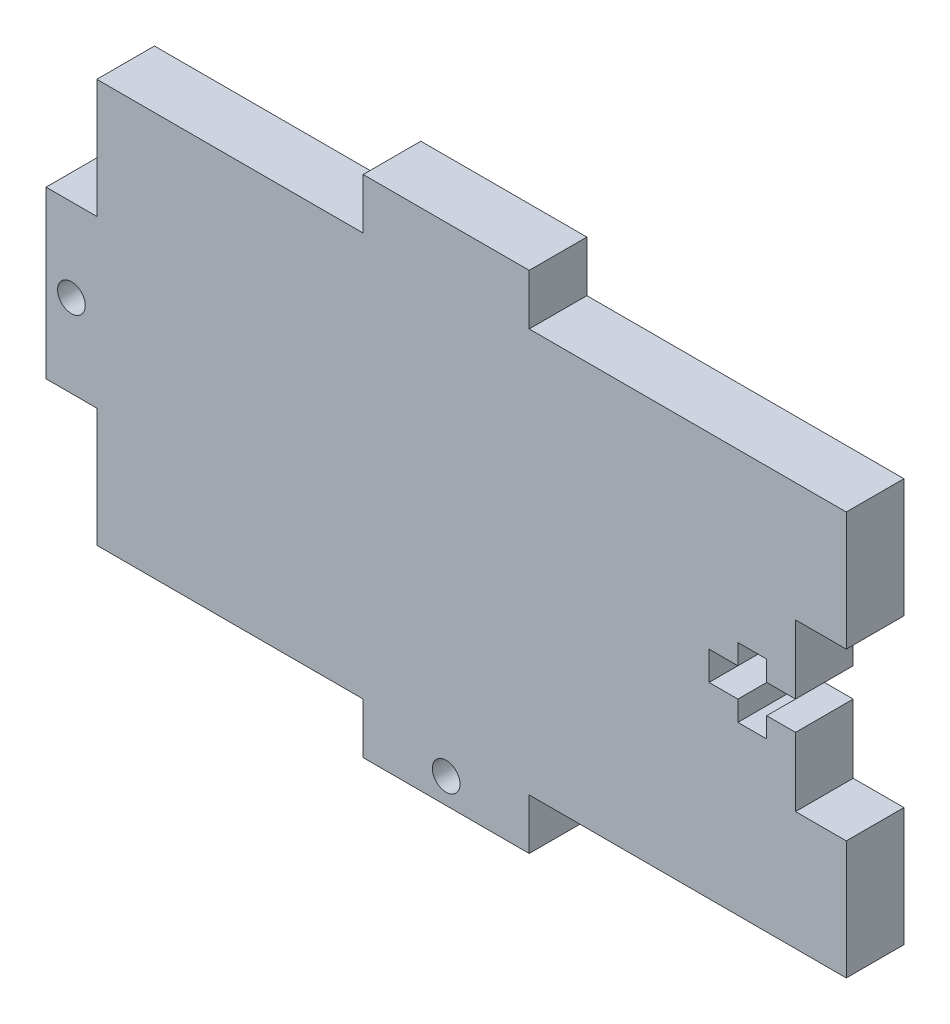
SolidWorks part; units mm, degrees
ref_plane "Front Plane" through (0, 0, 0) normal (0, 0, 1) x (1, 0, 0)
ref_plane "Top Plane" through (0, 0, 0) normal (0, 1, 0) x (1, 0, 0)
ref_plane "Right Plane" through (0, 0, 0) normal (1, 0, 0) x (0, 0, -1)
sketch "Sketch1" plane through (0, 0, 0) normal (0, 0, 1) x (1, 0, 0)
  line L1 (0, 0) -> (82.55, 0)
  line L2 (0, 0) -> (0, 44.45)
  line L3 (0, 44.45) -> (82.55, 44.45)
  line L4 (82.55, 0) -> (82.55, 44.45)
  dimension "D1" = 44.45
  dimension "D2" = 82.55
extrude "Boss-Extrude1" add sketch "Sketch1" along normal blind 6.35
sketch "Sketch2" plane through (0, 0, 6.35) normal (0, 0, 1) x (1, 0, 0)
  line L0 (0, -1.7462) -> (0, 1.7462) construction
  line L1 (0, 31.369) -> (-5.588, 31.369)
  line L2 (0, 31.369) -> (0, 13.081)
  line L3 (0, 13.081) -> (-5.588, 13.081)
  line L4 (-5.588, 31.369) -> (-5.588, 13.081)
  line L6 (0, 44.45) -> (0, 0) construction
  point P6 (-5.588, 22.225)
  point P7 (0, 22.225)
  dimension "D1" = 5.588
  dimension "D2" = 18.288
extrude "Boss-Extrude2" add sketch "Sketch2" against normal blind 6.35
sketch "Sketch5" plane through (0, 0, 6.35) normal (0, 0, 1) x (1, 0, 0)
  line L0 (82.55, 44.45) -> (0, 44.45) construction
  line L1 (29.337, 44.45) -> (47.625, 44.45)
  line L2 (29.337, 44.45) -> (29.337, 50.038)
  line L3 (29.337, 50.038) -> (47.625, 50.038)
  line L4 (47.625, 44.45) -> (47.625, 50.038)
  line L6 (-5.588, 22.225) -> (82.55, 22.225) construction
  line L7 (47.625, 0) -> (47.625, -5.588)
  line L8 (29.337, -5.588) -> (47.625, -5.588)
  line L9 (29.337, 0) -> (29.337, -5.588)
  line L10 (29.337, 0) -> (47.625, 0)
  line L13 (-5.588, 31.369) -> (-5.588, 13.081) construction
  line L14 (82.55, 0) -> (82.55, 44.45) construction
  point P12 (38.481, 0)
  point P18 (38.481, 22.225)
  point P19 (38.481, 44.45)
  dimension "D1" = 18.288
  dimension "D2" = 5.588
extrude "Boss-Extrude3" add sketch "Sketch5" against normal blind 6.35
sketch "Sketch3" plane through (0, 0, 6.35) normal (0, 0, 1) x (1, 0, 0)
  line L0 (82.55, 0) -> (82.55, 44.45) construction
  line L1 (82.55, 13.081) -> (76.962, 13.081)
  line L2 (82.55, 13.081) -> (82.55, 31.369)
  line L3 (82.55, 31.369) -> (76.962, 31.369)
  line L4 (76.962, 13.081) -> (76.962, 31.369)
  line L22 (0, 44.45) -> (0, 31.369)
  line L23 (0, 31.369) -> (-5.588, 31.369)
  line L24 (-5.588, 31.369) -> (-5.588, 13.081)
  line L25 (-5.588, 13.081) -> (0, 13.081)
  line L26 (0, 13.081) -> (0, 0)
  line L27 (0, 0) -> (29.337, 0)
  line L28 (29.337, 0) -> (29.337, -5.588)
  line L29 (29.337, -5.588) -> (47.625, -5.588)
  line L30 (47.625, -5.588) -> (47.625, 0)
  line L31 (47.625, 0) -> (82.55, 0)
  line L32 (82.55, 0) -> (82.55, 44.45)
  line L33 (82.55, 44.45) -> (47.625, 44.45)
  line L34 (47.625, 44.45) -> (47.625, 50.038)
  line L35 (47.625, 50.038) -> (29.337, 50.038)
  line L36 (29.337, 50.038) -> (29.337, 44.45)
  line L37 (29.337, 44.45) -> (0, 44.45)
  line L40 (-5.588, 31.369) -> (-5.588, 13.081) construction
  point P6 (76.962, 22.225)
  point P11 (-5.588, 22.225)
  dimension "D1" = 18.288
  dimension "D2" = 5.588
  dimension "D4" = 0
extrude "Cut-Extrude1" cut sketch "Sketch3" against normal through all
sketch "Sketch6" plane through (0, 0, 6.35) normal (0, 0, 1) x (1, 0, 0)
  line L0 (76.962, 31.369) -> (76.962, 13.081) construction
  line L1 (67.437, 23.8125) -> (70.612, 23.8125)
  line L2 (67.437, 23.8125) -> (67.437, 20.6375)
  line L3 (67.437, 20.6375) -> (70.612, 20.6375)
  line L4 (76.962, 23.8125) -> (76.962, 20.6375)
  line L5 (67.437, 23.8125) -> (76.962, 20.6375) construction
  line L6 (67.437, 20.6375) -> (76.962, 23.8125) construction
  line L7 (70.612, 18.415) -> (73.787, 18.415)
  line L8 (70.612, 18.415) -> (70.612, 20.6375)
  line L9 (70.612, 26.035) -> (73.787, 26.035)
  line L10 (73.787, 18.415) -> (73.787, 20.6375)
  line L11 (70.612, 18.415) -> (73.787, 26.035) construction
  line L12 (70.612, 26.035) -> (73.787, 18.415) construction
  line L13 (70.612, 23.8125) -> (70.612, 26.035)
  line L14 (73.787, 23.8125) -> (76.962, 23.8125)
  line L15 (73.787, 23.8125) -> (73.787, 26.035)
  line L16 (73.787, 20.6375) -> (76.962, 20.6375)
  line L17 (-2.794, 31.369) -> (-2.794, 13.081) construction
  line L18 (0, 31.369) -> (-5.588, 31.369) construction
  line L19 (-5.588, 13.081) -> (0, 13.081) construction
  line L20 (29.337, 50.038) -> (29.337, 44.45) construction
  line L21 (47.625, 44.45) -> (47.625, 50.038) construction
  line L22 (47.625, -5.588) -> (47.625, 0) construction
  line L23 (29.337, 0) -> (29.337, -5.588) construction
  line L24 (29.337, 50.038) -> (29.337, 44.45) construction
  line L25 (47.625, 44.45) -> (47.625, 50.038) construction
  line L26 (47.625, -5.588) -> (47.625, 0) construction
  line L27 (29.337, 0) -> (29.337, -5.588) construction
  line L28 (29.337, 47.244) -> (47.625, 47.244) construction
  line L29 (29.337, -2.794) -> (47.625, -2.794) construction
  circle A0 centre (-2.794, 22.225) radius 1.524
  circle A1 centre (38.481, -2.794) radius 1.524
  point P0 (72.1995, 22.225)
  point P5 (72.1995, 22.225)
  point P12 (76.962, 22.225)
  dimension "D4" = 3.048
  dimension "D6" = 3.048
  dimension "D1" = 3.175
  dimension "D2" = 7.62
  dimension "1/8" = 3.175
  dimension "D3" = 9.525
extrude "Cut-Extrude2" cut sketch "Sketch6" against normal through all
